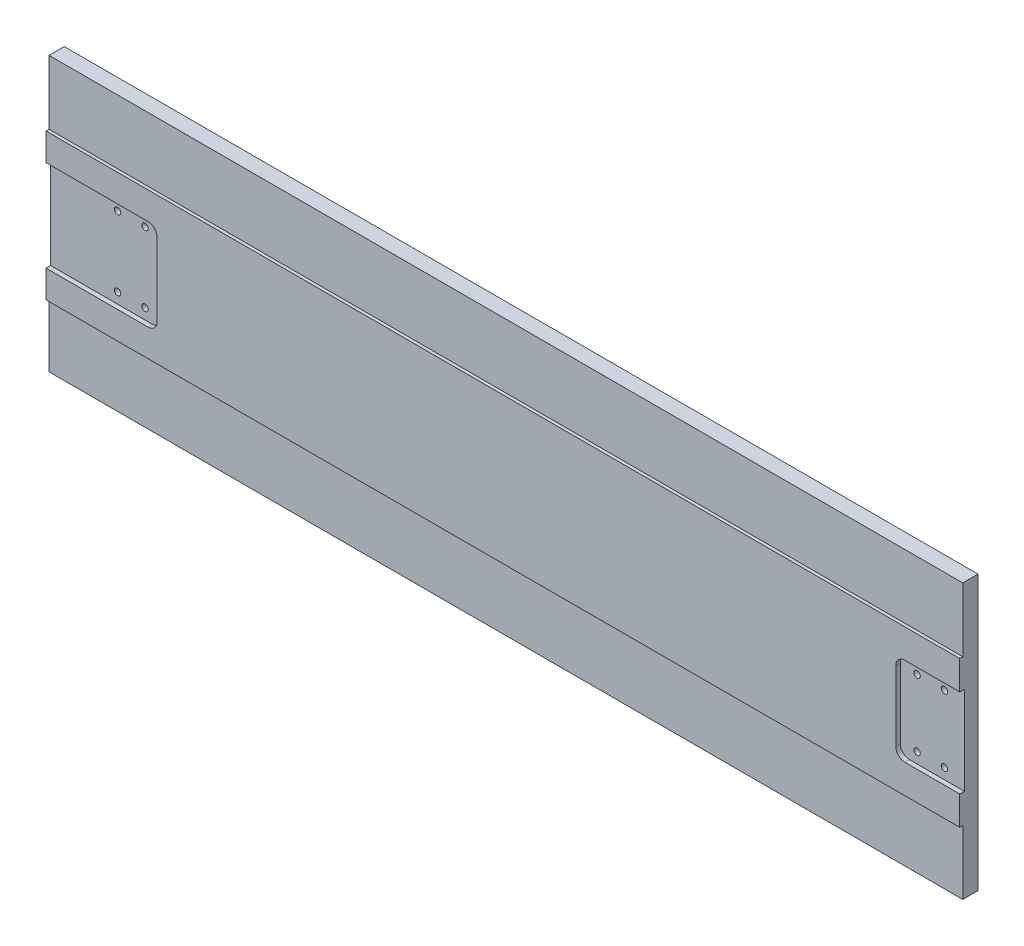
SolidWorks part; units mm, degrees
material "1.0037 (S235JR)"
ref_plane "Płaszczyzna przednia" through (0, 0, 0) normal (0, 0, 1) x (1, 0, 0)
ref_plane "Płaszczyzna górna" through (0, 0, 0) normal (0, 1, 0) x (1, 0, 0)
ref_plane "Płaszczyzna prawa" through (0, 0, 0) normal (1, 0, 0) x (0, 0, -1)
sketch "Szkic1" plane through (0, 0, 0) normal (0, 0, 1) x (1, 0, 0)
  line L1 (0, 450) -> (600, 450)
  line L2 (0, 450) -> (0, 270)
  line L3 (0, 270) -> (600, 270)
  line L4 (600, 450) -> (600, 270)
  line L6 (0, 430) -> (0, -20) construction
  line L7 (600, 430) -> (600, -20) construction
  line L8 (520, 430) -> (80, 430) construction
  dimension "D1" = 180
  dimension "D2" = 20
extrude "Dodanie-wyciągnięcie1" add sketch "Szkic1" along normal blind 10
sketch "Szkic2" plane through (0, 0, 10) normal (0, 0, 1) x (1, 0, 0)
  line L1 (0, 450) -> (0, 270) construction
  line L3 (0, 408) -> (600, 408)
  line L4 (0, 408) -> (0, 312)
  line L5 (600, 270) -> (600, 450) construction
  line L6 (0, 360) -> (600, 360) construction
  line L7 (0, 312) -> (600, 312)
  line L8 (600, 408) -> (600, 312)
  dimension "D1" = 96
extrude "Dodanie-wyciągnięcie2" add sketch "Szkic2" along normal blind 2
sketch "Szkic3" plane through (0, 0, 12) normal (0, 0, 1) x (1, 0, 0)
  line L0 (600, 312) -> (600, 408) construction
  line L1 (0, 360) -> (73, 360) construction
  line L2 (0, 408) -> (0, 312) construction
  line L3 (600, 331) -> (558, 331)
  line L4 (0, 390) -> (73, 390)
  line L5 (0, 390) -> (0, 330)
  line L6 (0, 330) -> (73, 330)
  line L7 (73, 390) -> (73, 330)
  line L8 (600, 331) -> (600, 389)
  line L9 (600, 389) -> (558, 389)
  line L10 (558, 331) -> (558, 389)
  line L11 (558, 360) -> (600, 360) construction
  dimension "D1" = 60
  dimension "D2" = 73
  dimension "D3" = 58
  dimension "D4" = 42
extrude "Wytnij-wyciągnięcie1" cut sketch "Szkic3" against normal blind 3
fillet "Zaokrąglenie1" radius 6 4 edges at (73, 330, 10.5) (73, 390, 10.5) (558, 331, 10.5) (558, 389, 10.5)
hole_wizard "Otwór gwintowany M5x0.82" positions "Szkic7" profile "Szkic6" tap size "M5x0.8" standard "Ansi Metric" end condition through all
sketch "Szkic7" plane through (0, 0, 9) normal (0, 0, 1) x (1, 0, 0)
  point P0 (62, 383)
  point P3 (44, 383)
  point P6 (62, 337)
  point P9 (44, 337)
sketch "Szkic6" plane through (62, 383, 9) normal (1, 0, 0) x (0, -1, 0)
  line L0 (0, 0) -> (0, 9)
  line L1 (0, 9) -> (2.1, 9)
  line L2 (2.1, 9) -> (2.1, 0)
  line L5 (2.1, 0) -> (0, 0)
  line L11 (0, -6.35) -> (0, 107.95) construction
  dimension "Średnica zewnętrzna gwintu" = 4.2
  dimension "Głębokość otworu gwintowanego na wylot" = 9
hole_wizard "Otwór gwintowany M5x0.83" positions "Szkic9" profile "Szkic8" tap size "M5x0.8" standard "Ansi Metric"
sketch "Szkic9" plane through (0, 0, 9) normal (0, 0, 1) x (1, 0, 0)
  point P0 (587, 382)
  point P3 (569, 382)
  point P6 (569, 338)
  point P9 (587, 338)
sketch "Szkic8" plane through (587, 382, 9) normal (1, 0, 0) x (0, -1, 0)
  line L0 (0, 0) -> (0, 18.2618)
  line L1 (0, 18.2618) -> (2.1, 17)
  line L2 (2.1, 17) -> (2.1, 0)
  line L5 (2.1, 0) -> (0, 0)
  line L10 (0, 18.2618) -> (-2.1, 17) construction
  line L11 (0, -6.35) -> (0, 107.95) construction
  dimension "Średnica wiertła gwintu" = 4.2
  dimension "Głębokość otworu gwintowanego" = 17
  dimension "Kąt wiertła" = 118
